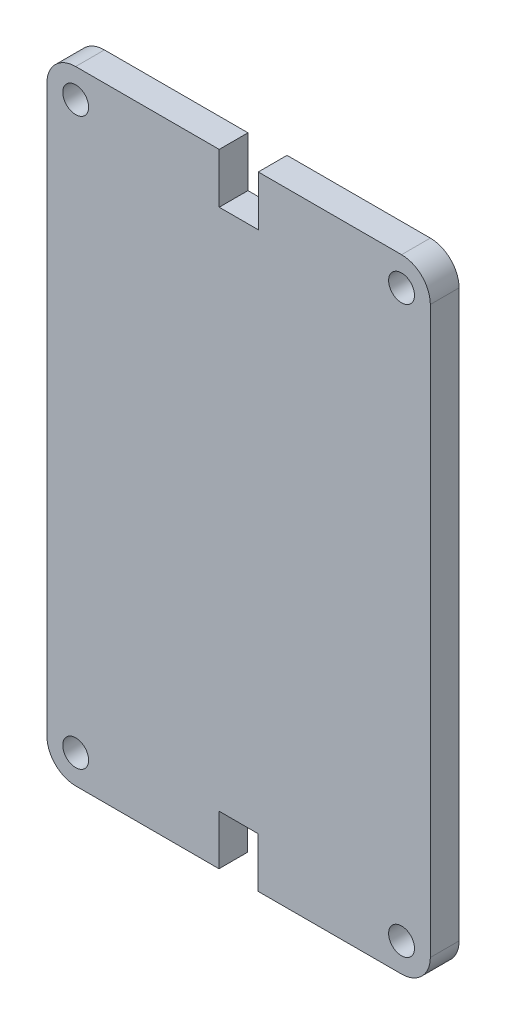
SolidWorks part; units mm, degrees
ref_plane "Front Plane" through (0, 0, 0) normal (0, 0, 1) x (1, 0, 0)
ref_plane "Top Plane" through (0, 0, 0) normal (0, 1, 0) x (1, 0, 0)
ref_plane "Right Plane" through (0, 0, 0) normal (1, 0, 0) x (0, 0, -1)
sketch "Sketch1" plane through (0, 0, 0) normal (0, 0, 1) x (1, 0, 0)
  line L12 (3, 0) -> (17.95, -0.01)
  line L13 (17.95, -0.01) -> (17.95, 5.2)
  line L14 (17.95, 5.2) -> (22.025, 5.2)
  line L15 (22.025, 5.2) -> (22.025, -0.01)
  line L16 (22.025, -0.01) -> (37, 0)
  line L17 (40, 3) -> (40, 62)
  line L18 (37, 65) -> (22.05, 65)
  line L19 (22.05, 65) -> (22.05, 59.775)
  line L20 (22.05, 59.775) -> (17.975, 59.775)
  line L21 (17.975, 59.775) -> (17.975, 65)
  line L22 (17.975, 65) -> (3, 65)
  line L23 (0, 62) -> (0, 3)
  line L24 (3, 0) -> (17.95, -0.01)
  line L25 (17.95, -0.01) -> (17.95, 5.2)
  line L26 (17.95, 5.2) -> (22.025, 5.2)
  line L27 (22.025, 5.2) -> (22.025, -0.01)
  line L28 (22.025, -0.01) -> (37, 0)
  line L29 (40, 3) -> (40, 62)
  line L30 (37, 65) -> (22.05, 65)
  line L31 (22.05, 65) -> (22.05, 59.775)
  line L32 (22.05, 59.775) -> (17.975, 59.775)
  line L33 (17.975, 59.775) -> (17.975, 65)
  line L34 (17.975, 65) -> (3, 65)
  line L35 (0, 62) -> (0, 3)
  arc A4 (0, 3) -> (3, 0) centre (3, 3) ccw
  arc A5 (37, 0) -> (40, 3) centre (37, 3) ccw
  arc A6 (40, 62) -> (37, 65) centre (37, 62) ccw
  arc A7 (3, 65) -> (0, 62) centre (3, 62) ccw
  arc A8 (0, 3) -> (3, 0) centre (3, 3) ccw
  arc A9 (37, 0) -> (40, 3) centre (37, 3) ccw
  arc A10 (40, 62) -> (37, 65) centre (37, 62) ccw
  arc A11 (3, 65) -> (0, 62) centre (3, 62) ccw
  dimension "D1" = 0
extrude "Boss-Extrude1" add sketch "Sketch1" along normal blind 3 contours A8 L24 L25 L26 L27 L28 A9 L29 A10 L30 L31 L32 L33 L34 A11 L35
sketch "Sketch2" plane through (0, 0, 3) normal (0, 0, 1) x (1, 0, 0)
  circle A0 centre (3, 3) radius 1.35 construction
  circle A1 centre (37, 3) radius 1.35 construction
  circle A2 centre (37, 62) radius 1.35 construction
  circle A3 centre (3, 62) radius 1.35 construction
  circle A4 centre (3, 3) radius 1.35
  circle A5 centre (37, 3) radius 1.35
  circle A6 centre (37, 62) radius 1.35
  circle A7 centre (3, 62) radius 1.35
extrude "Cut-Extrude1" cut sketch "Sketch2" against normal through all
sketch "Sketch12" plane through (0, 0, 3) normal (0, 0, 1) x (1, 0, 0)
  circle A2 centre (3, 62) radius 2.85
  circle A3 centre (3, 62) radius 2.85
  circle A10 centre (37, 62) radius 2.85
  circle A11 centre (37, 62) radius 2.85
  circle A13 centre (37, 3) radius 2.85
  circle A14 centre (37, 3) radius 2.85
  circle A16 centre (3, 3) radius 2.85
  circle A17 centre (3, 3) radius 2.85
  dimension "D1" = 1.5
  dimension "D2" = 1.5
  dimension "D3" = 1.5
  dimension "D4" = 1.5
sketch "Sketch18" plane through (0, 0, 3) normal (0, 0, 1) x (1, 0, 0)
  line L12 (1.5, 63.5) -> (16.475, 63.5)
  line L13 (16.475, 63.5) -> (16.475, 58.275)
  line L14 (16.475, 58.275) -> (23.55, 58.275)
  line L15 (23.55, 58.275) -> (23.55, 63.5)
  line L16 (23.55, 63.5) -> (38.5, 63.5)
  line L17 (1.5, 63.5) -> (1.5, 1.495)
  line L18 (38.5, 63.5) -> (38.5, 1.495)
  line L19 (0, 62) -> (0, 3) construction
  line L20 (17.975, 65) -> (3, 65) construction
  line L21 (17.975, 59.775) -> (17.975, 65) construction
  line L22 (22.05, 65) -> (22.05, 59.775) construction
  line L23 (22.05, 59.775) -> (17.975, 59.775) construction
  line L24 (37, 65) -> (22.05, 65) construction
  line L25 (40, 3) -> (40, 62) construction
  line L26 (1.5, 1.495) -> (16.45, 1.495)
  line L27 (16.45, 1.495) -> (16.45, 6.7)
  line L28 (16.45, 6.7) -> (23.525, 6.7)
  line L29 (23.525, 6.7) -> (23.525, 1.495)
  line L30 (23.525, 1.495) -> (38.5, 1.495)
  line L32 (3, 0) -> (17.95, -0.01) construction
  line L33 (17.95, -0.01) -> (17.95, 5.2) construction
  line L34 (17.95, 5.2) -> (22.025, 5.2) construction
  line L35 (22.025, 5.2) -> (22.025, -0.01) construction
  line L36 (22.025, -0.01) -> (37, 0) construction
  point P28 (10.475, -0.005)
  point P37 (29.5125, -0.005)
  dimension "D1" = 1.5
  dimension "D2" = 1.5
  dimension "D3" = 1.5
  dimension "D4" = 1.5
  dimension "D5" = 1.5
  dimension "D6" = 1.5
  dimension "D7" = 1.5
  dimension "D8" = 1.5
  dimension "D9" = 1.5
  dimension "D10" = 1.5
  dimension "D11" = 1.5
  dimension "D12" = 1.5
sketch "Sketch19" plane through (0, 0, 3) normal (0, 0, 1) x (1, 0, 0)
equation "\"RibWidth\"= 1.5"
equation "\"D1@Sketch18\"=\"RibWidth\""
equation "\"D2@Sketch18\"=\"RibWidth\""
equation "\"D3@Sketch18\"=\"RibWidth\""
equation "\"D4@Sketch18\"=\"RibWidth\""
equation "\"D5@Sketch18\"=\"RibWidth\""
equation "\"D6@Sketch18\"=\"RibWidth\""
equation "\"D7@Sketch18\"=\"RibWidth\""
equation "\"D8@Sketch18\"=\"RibWidth\""
equation "\"D9@Sketch18\"=\"RibWidth\""
equation "\"D10@Sketch18\"=\"RibWidth\""
equation "\"D11@Sketch18\"=\"RibWidth\""
equation "\"D12@Sketch18\"=\"RibWidth\""
